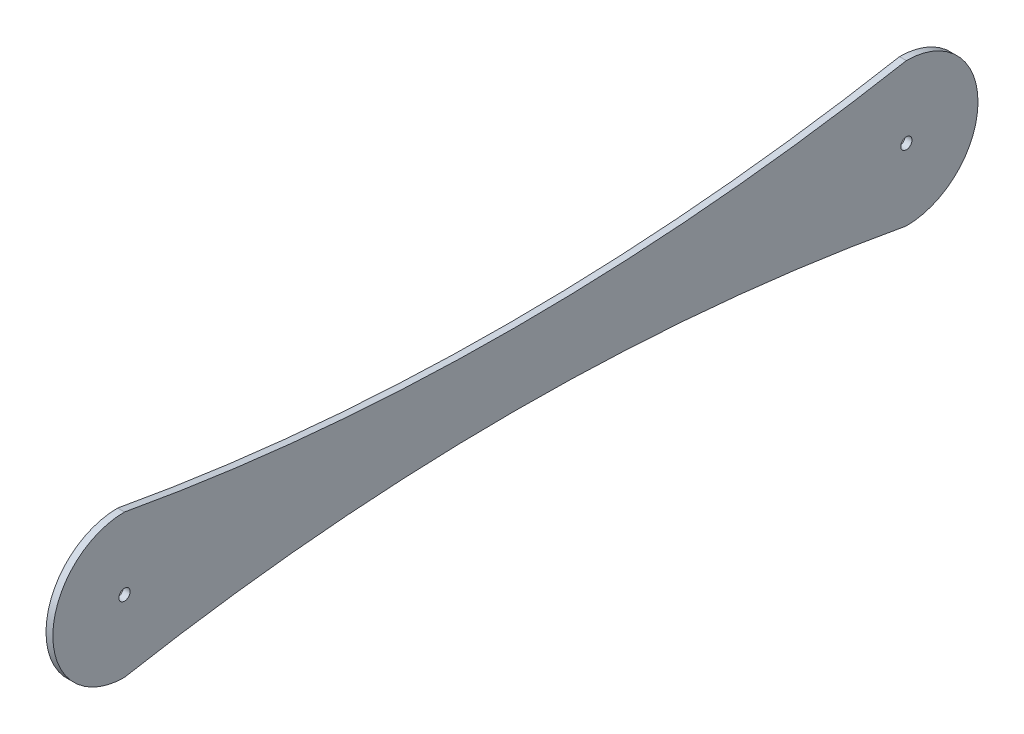
SolidWorks part; units mm, degrees
ref_plane "Front Plane" through (0, 0, 0) normal (0, 0, 1) x (1, 0, 0)
ref_plane "Top Plane" through (0, 0, 0) normal (0, 1, 0) x (1, 0, 0)
ref_plane "Right Plane" through (0, 0, 0) normal (1, 0, 0) x (0, 0, -1)
sketch "Sketch1" plane through (0, 0, 0) normal (1, 0, 0) x (0, 0, -1)
  line L0 (0, -15.9695) -> (0, 0) construction
  line L5 (-198.755, 31.75) -> (198.755, -31.75) construction
  line L6 (-198.755, -31.75) -> (198.755, 31.75) construction
  line L7 (0, 0) -> (0, 15.9695) construction
  circle A0 centre (-173.355, 0) radius 2.4892
  circle A1 centre (173.355, 0) radius 2.4892
  arc A2 (-173.355, 31.75) -> (-173.355, -31.75) centre (-173.355, 0) ccw
  arc A3 (173.355, 31.75) -> (173.355, -31.75) centre (173.355, 0) cw
  arc A4 (-173.355, -31.75) -> (173.355, -31.75) centre (0, -976.0465) cw
  arc A5 (-173.355, 31.75) -> (173.355, 31.75) centre (0, 976.0465) ccw
  point P0 (0, 0)
  point P6 (-198.755, 25.4)
  point P7 (198.755, 25.4)
  point P10 (-173.355, 31.75)
  point P13 (-173.355, -31.75)
  point P14 (173.355, 31.75)
  point P15 (173.355, -31.75)
  point P24 (0, 7.9848)
  point P26 (0, -7.9848)
  dimension "D1" = 397.51
  dimension "D2" = 63.5
extrude "Boss-Extrude1" add sketch "Sketch1" along normal blind 3.0378
